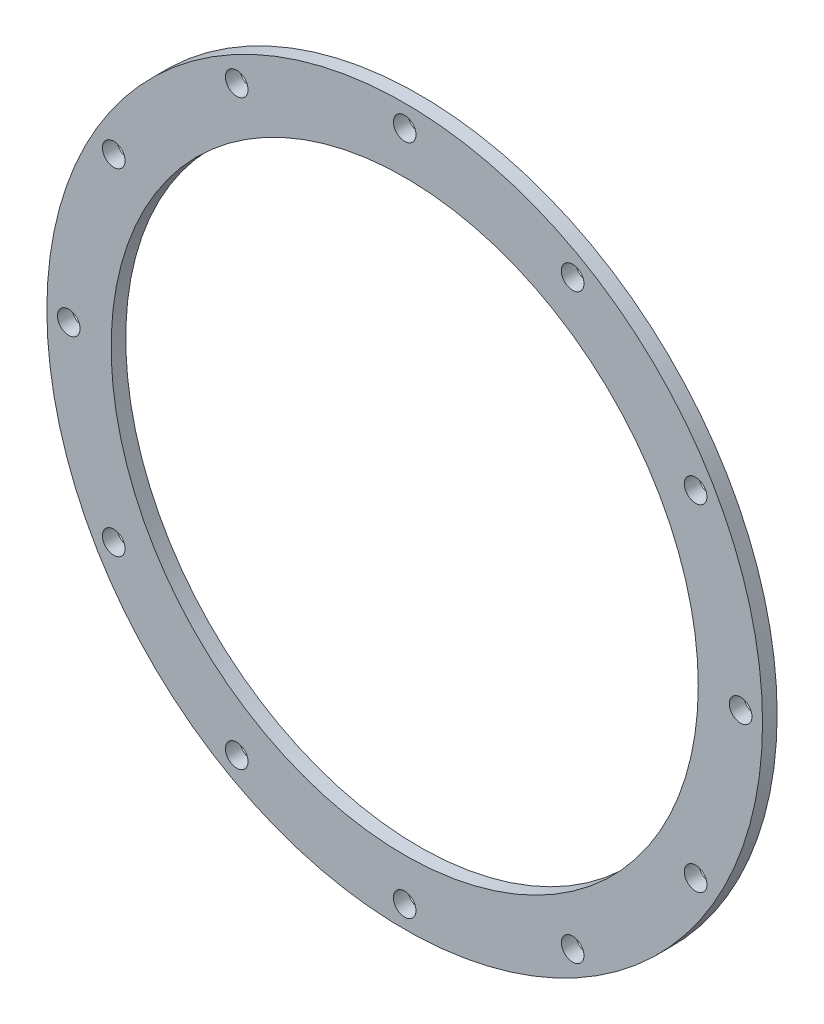
SolidWorks part; units mm, degrees
material "Thornel Mat VMA"
ref_plane "前视基准面" through (0, 0, 0) normal (0, 0, 1) x (1, 0, 0)
ref_plane "上视基准面" through (0, 0, 0) normal (0, 1, 0) x (1, 0, 0)
ref_plane "右视基准面" through (0, 0, 0) normal (1, 0, 0) x (0, 0, -1)
sketch "草图1" plane through (0, 0, 0) normal (0, 0, 1) x (1, 0, 0)
  line L0 (0, 0) -> (0, 46) construction
  line L1 (0, 0) -> (23, 39.8372) construction
  circle A0 centre (0, 0) radius 43 construction
  circle A1 centre (0, 0) radius 40.2
  circle A2 centre (0, 0) radius 49
  circle A3 centre (0, 0) radius 46 construction
  circle A4 centre (0, 46) radius 1.55
  circle A5 centre (23, 39.8372) radius 1.55
  circle A6 centre (39.8372, 23) radius 1.55
  circle A7 centre (46, 0) radius 1.55
  circle A8 centre (39.8372, -23) radius 1.55
  circle A9 centre (23, -39.8372) radius 1.55
  circle A10 centre (0, -46) radius 1.55
  circle A11 centre (-23, -39.8372) radius 1.55
  circle A12 centre (-39.8372, -23) radius 1.55
  circle A13 centre (-46, 0) radius 1.55
  circle A14 centre (-39.8372, 23) radius 1.55
  circle A15 centre (-23, 39.8372) radius 1.55
  dimension "D1" = 86
  dimension "D3" = 98
  dimension "D5" = 3.1
  dimension "D7" = 30
  dimension "D2" = 2.8
  dimension "D4" = 3
  dimension "D6" = 12
extrude "凸台-拉伸1" add sketch "草图1" along normal blind 2
